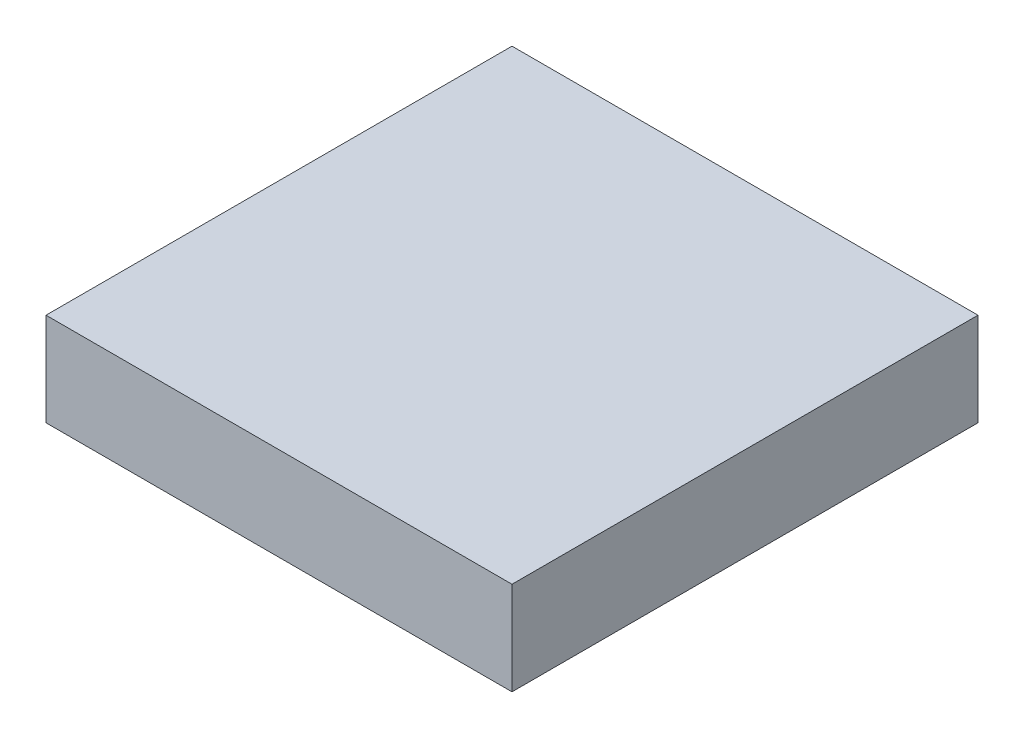
SolidWorks part; units mm, degrees
ref_plane "前基準面" through (0, 0, 0) normal (0, 0, 1) x (1, 0, 0)
ref_plane "上基準面" through (0, 0, 0) normal (0, 1, 0) x (1, 0, 0)
ref_plane "右基準面" through (0, 0, 0) normal (1, 0, 0) x (0, 0, -1)
sketch "草圖1" plane through (0, 0, 0) normal (0, 1, 0) x (1, 0, 0)
  line L1 (-50000, 50000) -> (50000, 50000)
  line L2 (-50000, 50000) -> (-50000, -50000)
  line L3 (-50000, -50000) -> (50000, -50000)
  line L4 (50000, 50000) -> (50000, -50000)
  line L5 (-50000, 50000) -> (50000, -50000) construction
  line L6 (-50000, -50000) -> (50000, 50000) construction
  point P0 (0, 0)
  dimension "D1" = 100000
  dimension "D2" = 100000
extrude "填料-伸長1" add sketch "草圖1" along normal blind 20000
sketch "草圖3" plane through (0, 20000, 0) normal (0, 1, 0) x (1, 0, 0)
  line L0 (2449.0699, 130) -> (2578.4032, 130) construction
  arc A0 (-29105.4851, 43381.7603) -> (-22513.7321, 43041.3452) centre (-25400.0266, 51142.6458) ccw
  arc A1 (-22513.7321, 43041.3452) -> (-14536.792, 42779.1717) centre (-18829.5782, 33651.0803) cw
  arc A2 (-14536.792, 42779.1717) -> (-3695.8779, 43506.8283) centre (-7260.9677, 15501.0079) cw
  arc A3 (-3695.8779, 43506.8283) -> (1352.1133, 42347.1617) centre (-6998.1933, 17565.2513) cw
  arc A4 (1352.1133, 42347.1617) -> (7148.3877, 43044.0259) centre (7525.2416, 15455.3568) cw
  arc A5 (7148.3877, 43044.0259) -> (12457.5315, 41672.1063) centre (7290.5662, 32635.4429) cw
  arc A6 (12457.5315, 41672.1063) -> (14953.6735, 41672.1063) centre (13705.6025, 36942.5301) cw
  arc A7 (14953.6735, 41672.1063) -> (18667.8152, 43506.8283) centre (18311.6769, 39551.0364) cw
  arc A8 (18667.8152, 43506.8283) -> (22238.7241, 42033.3771) centre (18201.3606, 37312.6012) cw
  arc A9 (22238.7241, 42033.3771) -> (29716.1549, 42347.1617) centre (27278.699, 11181.4874) cw
  arc A10 (29716.1549, 42347.1617) -> (32242.5936, 37954.4769) centre (28783.0318, 38887.5999) cw
  arc A11 (32242.5936, 37954.4769) -> (29995.6328, 35909.1671) centre (30096.4583, 38055.3024) cw
  arc A12 (29995.6328, 35909.1671) -> (31542.7107, 31311.9778) centre (21949.927, 30642.6592) cw
  arc A13 (31542.7107, 31311.9778) -> (29040.0967, 25527.1877) centre (27399.0086, 29670.8898) cw
  arc A14 (29040.0967, 25527.1877) -> (28132.4433, 18134.8066) centre (24890.0794, 22284.8238) cw
  arc A15 (28132.4433, 18134.8066) -> (27130.6958, 7974.3406) centre (19022.3591, 13903.3787) cw
  arc A16 (27130.6958, 7974.3406) -> (27069.5376, 3028.9099) centre (35169.4567, 5401.8348) ccw
  arc A17 (27069.5376, 3028.9099) -> (24890.0794, 0) centre (24465.3536, 2604.184) cw
  arc A18 (24890.0794, 0) -> (26358.4201, -9003.0526) centre (17636.501, -5804.2774) cw
  arc A19 (26358.4201, -9003.0526) -> (24890.0794, -9003.0526) centre (25624.2498, -2914.8344) cw
  arc A20 (24890.0794, -9003.0526) -> (23061.4881, -20661.1957) centre (-25102.1791, -7134.197) cw
  arc A21 (23061.4881, -20661.1957) -> (21291.7464, -30745.9262) centre (18755.9976, -25103.2858) cw
  arc A22 (21291.7464, -30745.9262) -> (17636.501, -29763.6444) centre (20311.0661, -27103.1619) cw
  arc A23 (17636.501, -29763.6444) -> (16918.6621, -26553.3663) centre (18882.7206, -27799.5859) cw
  arc A24 (16918.6621, -26553.3663) -> (18755.9976, -25103.2858) centre (22369.5189, -31570.8706) cw
  arc A25 (18755.9976, -25103.2858) -> (20078.5804, -19868.9386) centre (22034.4626, -23147.4036) cw
  arc A26 (20078.5804, -19868.9386) -> (14953.6735, -19868.9386) centre (17516.127, 13661.9951) cw
  arc A27 (14953.6735, -19868.9386) -> (14575.5901, -21851.0319) centre (4882.6917, -18975.0098) cw
  arc A28 (14575.5901, -21851.0319) -> (11354.9125, -22583.334) centre (11796.0795, -17075.1448) cw
  arc A29 (11354.9125, -22583.334) -> (10446.6749, -33923.1311) centre (36693.5677, -30319.0513) ccw
  arc A30 (10412.8915, -33667.9058) -> (12457.5315, -35195.4793) centre (10671.4247, -35454.0126) cw
  arc A31 (12457.5315, -35195.4793) -> (19709.455, -35944.3514) centre (15709.0572, -39195.8771) cw
  arc A32 (19709.455, -35944.3514) -> (17516.127, -40516.7731) centre (16326.5801, -37133.8982) cw
  arc A33 (17516.127, -40516.7731) -> (5997.892, -39195.8771) centre (14058.7976, -19784.6936) cw
  arc A34 (5997.892, -39195.8771) -> (6483.1135, -34402.7554) centre (7356.3466, -36912.2764) cw
  arc A35 (6483.1135, -34402.7554) -> (8373.5747, -22583.334) centre (28536.4528, -31869.188) cw
  arc A36 (8373.5747, -22583.334) -> (5997.892, -21489.2321) centre (8615.225, -18932.3503) cw
  arc A37 (5997.892, -21489.2321) -> (6090.5814, -20396.4657) centre (-20285.9311, -18709.5008) ccw
  arc A38 (6090.5814, -20396.4657) -> (-2629.315, -20708.0718) centre (694.8668, 8432.3284) cw
  arc A39 (-2629.315, -20708.0718) -> (-3067.8556, -22255.8072) centre (-4294.044, -21072.3783) cw
  arc A40 (-3067.8556, -22255.8072) -> (-4591.0985, -23023.3057) centre (-5901.519, -18527.2054) cw
  arc A41 (-4591.0985, -23023.3057) -> (-3067.8556, -34824.7987) centre (-24285.5333, -31564.3572) cw
  arc A42 (-3067.8556, -34824.7987) -> (-3598.2833, -40431.9885) centre (-3802.0014, -37584.0337) cw
  arc A43 (-3598.2833, -40431.9885) -> (-14803.703, -40787.1207) centre (-9776.1832, -22460.6937) cw
  arc A44 (-14803.703, -40787.1207) -> (-13972.893, -34402.7554) centre (-12745.8762, -37808.6696) cw
  arc A45 (-13972.893, -34402.7554) -> (-8918.8529, -35454.0126) centre (-12562.1291, -40294.9138) cw
  arc A46 (-8918.8529, -35454.0126) -> (-7260.9677, -34363.1794) centre (-2628.5001, -43209.0322) cw
  arc A47 (-7260.9677, -34363.1794) -> (-8117.0774, -23147.4036) centre (-35668.638, -30890.9993) ccw
  arc A48 (-8117.0774, -23147.4036) -> (-11328.3085, -22255.8072) centre (-6923.5915, -12620.1805) cw
  arc A49 (-11328.3085, -22255.8072) -> (-11222.4481, -20708.0718) centre (-10501.5106, -21534.8697) cw
  arc A50 (-11222.4481, -20708.0718) -> (-16093.8526, -20505.2635) centre (-12829.6228, -705.6337) cw
  arc A51 (-16201.4643, -20505.2635) -> (-16093.8526, -24740.0648) centre (-38908.1055, -23201.0359) cw
  arc A52 (-16093.8526, -24740.0648) -> (-13972.893, -27405.2099) centre (-18819.3533, -29085.5734) cw
  arc A53 (-13972.893, -27405.2099) -> (-18829.5782, -30745.9262) centre (-17496.6252, -27483.1064) cw
  arc A54 (-18829.5782, -30745.9262) -> (-22513.7321, -22460.6937) centre (-16529.0389, -24761.233) cw
  arc A55 (-22513.7321, -22460.6937) -> (-21071.759, -18709.5008) centre (-31826.5485, -16728.0645) ccw
  arc A56 (-21071.759, -18709.5008) -> (-23454.931, -9003.0526) centre (-4272.6988, -9439.1302) cw
  arc A57 (-23454.931, -9003.0526) -> (-26000.8598, -9229.2582) centre (-25419.2031, -1335.5343) cw
  arc A58 (-26000.8598, -9229.2582) -> (-25102.1791, -705.6337) centre (-4776.0866, -7157.8852) cw
  arc A59 (-25102.1791, -705.6337) -> (-25984.143, 5401.8348) centre (-19154.7372, 3270.6365) cw
  arc A60 (-25984.143, 5401.8348) -> (-25181.3615, 7974.3406) centre (-28969.0789, 7744.8317) ccw
  arc A61 (-25181.3615, 7974.3406) -> (-28148.6757, 13661.9951) centre (-23821.1914, 12301.8249) cw
  arc A62 (-28148.6757, 13661.9951) -> (-29297.0068, 20519.4536) centre (-32151.5705, 16516.5588) ccw
  arc A63 (-29297.0068, 20519.4536) -> (-28525.7657, 26747.544) centre (-18734.0953, 22373.2177) cw
  arc A64 (-28525.7657, 26747.544) -> (-29488.9165, 34144.4807) centre (-20666.5673, 31532.0596) cw
  arc A65 (-29488.9165, 34144.4807) -> (-31010.4971, 40008.4489) centre (-37796.0964, 35118.3301) ccw
  arc A66 (-31010.4971, 40008.4489) -> (-29105.4851, 43381.7603) centre (-29435.9622, 41343.8259) cw
  circle A67 centre (-4776.0866, 22373.2177) radius 1204.4664
  circle A68 centre (-4776.0866, 22373.2177) radius 3460.2799
  circle A69 centre (7946.9664, 21695.4559) radius 3026.4276
  circle A70 centre (7946.9664, 21695.4559) radius 1117.9253
  arc A71 (1279.3178, 20056.3891) -> (-17569.9428, 19809.9499) centre (-8168.2841, 21690.1851) ccw
  arc A72 (3960.5471, 15516.4433) -> (18093.0045, 15639.7674) centre (10973.394, 21695.4559) ccw
  arc A73 (0, 14877.7819) -> (326.693, 19807.6104) centre (4882.8634, 17029.9403) cw
  arc A74 (326.693, 19807.6104) -> (4559.2902, 18134.8066) centre (1606.5897, 16854.9099) cw
  arc A75 (4559.2902, 18134.8066) -> (1606.5897, 12863.8671) centre (-1729.6115, 18195.2553) cw
  arc A76 (-18734.0953, 16516.5588) -> (21291.7464, 15455.3568) centre (1697.0088, 31758.7676) ccw
  arc A77 (-4911.8585, 7140.1198) -> (-5115.6352, 3270.6365) centre (15385.7351, 4131.0902) ccw
  arc A78 (-5115.6352, 3270.6365) -> (-255.0248, 3270.6365) centre (-2685.33, 17921.851) ccw
  arc A79 (-255.0248, 3270.6365) -> (0, 6325.0281) centre (-7402.2093, 5405.2294) ccw
  arc A80 (2858.319, 6294.9442) -> (3026.6409, 2604.184) centre (-58411.4175, 1651.4411) cw
  arc A81 (3026.6409, 2604.184) -> (8373.5747, 2687.1009) centre (4462.4502, 82456.5555) ccw
  arc A82 (8373.5747, 2687.1009) -> (8157.1753, 7100.6818) centre (-16835.6692, 3663.1783) ccw
  arc A83 (-23454.931, 13661.9951) -> (-23454.931, 18195.2553) centre (-20059.2658, 15928.6252) cw
  arc A84 (-23454.931, 18195.2553) -> (-16529.0389, 19217.2628) centre (-19480.9812, 15243.313) cw
  arc A85 (-16529.0389, 19217.2628) -> (-16093.8526, 15501.0079) centre (-18169.5732, 17141.5422) cw
  arc A86 (18201.3606, 15455.3568) -> (19022.3591, 19217.2628) centre (20492.8129, 16925.8106) cw
  arc A87 (19022.3591, 19217.2628) -> (26358.4201, 15928.6252) centre (21046.0708, 13904.9135) cw
  arc A88 (26358.4201, 15928.6252) -> (24890.0794, 12863.8671) centre (24091.8707, 15130.4165) cw
  arc A89 (-15823.8052, 15917.8833) -> (-373.0148, 16108.0485) centre (-8168.2841, 21690.1851) ccw
  arc A90 (20059.3748, 19503.3861) -> (1769.3343, 20068.9557) centre (10973.394, 21695.4559) ccw
  arc A91 (-16201.4643, -20505.2635) -> (-18555.454, -19596.4287) centre (-19685.9156, -26027.4308) ccw
  arc A92 (-18555.454, -19596.4287) -> (-21071.759, -7977.7278) centre (1712.4728, -9125.0956) cw
  arc A93 (-21071.759, -7977.7278) -> (-11222.4481, -7157.8852) centre (-15412.4623, -16393.5386) cw
  arc A94 (-11222.4481, -7157.8852) -> (-7402.2093, -7157.8852) centre (-9312.3287, -36929.1395) cw
  arc A95 (-7402.2093, -7157.8852) -> (-2629.315, -9833.151) centre (-1854.2555, -2855.1303) ccw
  arc A96 (-2629.315, -9833.151) -> (0, -7540.2243) centre (-2461.1208, -7372.0302) ccw
  arc A97 (0, -7540.2243) -> (-7402.2093, -7157.8852) centre (-3892.2742, -11050.1594) ccw
  arc A98 (0, -7540.2243) -> (3517.859, -7722.9799) centre (274.0406, -36214.2131) cw
  arc A99 (3517.859, -7722.9799) -> (9922.1156, -7722.9799) centre (6719.9873, -12520.694) cw
  arc A100 (9922.1156, -7722.9799) -> (6090.5814, -10164.8348) centre (6785.421, -7028.1402) cw
  arc A101 (6090.5814, -10164.8348) -> (3517.859, -7722.9799) centre (6025.1476, -7657.5461) cw
  arc A102 (3825.0765, -8861.8986) -> (3026.6409, -10165.6884) centre (2773.9637, -9114.5757) cw
  arc A103 (3026.6409, -10165.6884) -> (2933.177, -11050.1594) centre (-4164.5352, -9852.9561) cw
  arc A104 (2933.177, -11050.1594) -> (4298.4955, -15127.1686) centre (-39022.4935, -27367.4885) cw
  arc A105 (4298.4955, -15127.1686) -> (1712.4728, -18280.5561) centre (-4399.2625, -10631.395) cw
  arc A106 (1712.4728, -18280.5561) -> (-1525.0347, -15349.6191) centre (8507.6983, -7521.0218) cw
  arc A107 (-1525.0347, -15349.6191) -> (274.0406, -11050.1594) centre (9107.5959, -17272.6258) cw
  arc A108 (274.0406, -11050.1594) -> (274.0406, -10050.1955) centre (10197.2458, -10550.1775) cw
  arc A109 (274.0406, -10050.1955) -> (-698.5183, -9097.9031) centre (721.3391, -8620.6032) cw
  arc A110 (9922.1156, -7722.9799) -> (15709.0572, -7158.4086) centre (11967.7099, 1250.1703) ccw
  arc A111 (15709.0572, -7158.4086) -> (22034.4626, -7448.2741) centre (18540.2403, -14537.7183) cw
  arc A112 (22034.4626, -7448.2741) -> (20078.5804, -19868.9386) centre (5924.4309, -11275.7558) cw
  arc A113 (-20916.2847, -12019.4012) -> (-542.5441, -12412.0101) centre (774.9517, 584782.9573) ccw
  arc A114 (3436.1132, -12407.5342) -> (22466.1881, -12019.4012) centre (774.9517, 584782.9573) ccw
